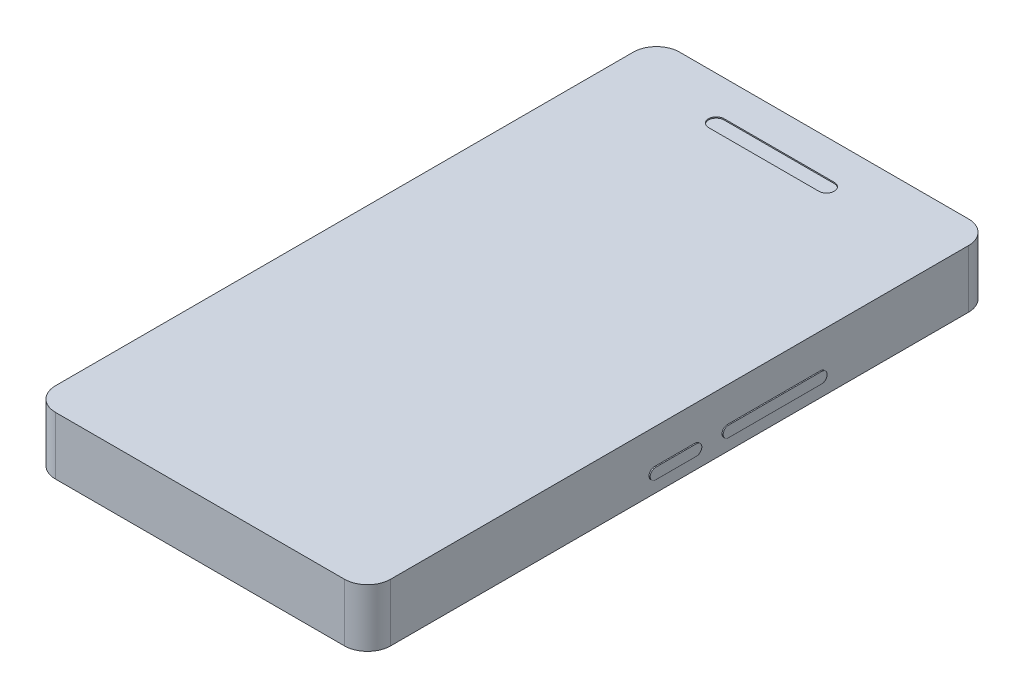
SolidWorks part; units mm, degrees
ref_plane "Front Plane" through (0, 0, 0) normal (0, 0, 1) x (1, 0, 0)
ref_plane "Top Plane" through (0, 0, 0) normal (0, 1, 0) x (1, 0, 0)
ref_plane "Right Plane" through (0, 0, 0) normal (1, 0, 0) x (0, 0, -1)
sketch "Sketch2" plane through (0, 0, 0) normal (0, 1, 0) x (1, 0, 0)
  line L1 (23.3045, 59.8762) -> (-40.1955, 59.8762)
  line L2 (28.3845, 54.7962) -> (28.3845, -72.2038)
  line L3 (23.3045, -77.2838) -> (-40.1955, -77.2838)
  line L4 (-45.2755, 54.7962) -> (-45.2755, -72.2038)
  line L5 (28.3845, 59.8762) -> (27.3244, 57.9021) construction
  line L7 (-44.2154, 57.9021) -> (-45.2755, 59.8762) construction
  arc A0 (23.3045, 59.8762) -> (28.3845, 54.7962) centre (23.3045, 54.7962) cw
  arc A1 (28.3845, -72.2038) -> (23.3045, -77.2838) centre (23.3045, -72.2038) cw
  arc A2 (-40.1955, -77.2838) -> (-45.2755, -72.2038) centre (-40.1955, -72.2038) cw
  arc A3 (-40.1955, 59.8762) -> (-45.2755, 54.7962) centre (-40.1955, 54.7962) ccw
  point P0 (-8.4455, -8.7038)
  dimension "D1" = 5.08
  dimension "D2" = 63.5
  dimension "D3" = 127
extrude "Boss-Extrude1" add sketch "Sketch2" along normal blind 12.7
sketch "Sketch5" plane through (0, 0, 0) normal (0, -1, 0) x (-1, 0, 0)
  line L0 (8.2564, 20.3242) -> (8.2564, 47.1774) construction
  line L1 (1.2594, 20.3242) -> (1.2594, 47.1774)
  line L2 (15.2534, 20.3242) -> (15.2534, 47.1774)
  arc A0 (1.2594, 20.3242) -> (15.2534, 20.3242) centre (8.2564, 20.3242) ccw
  arc A1 (15.2534, 47.1774) -> (1.2594, 47.1774) centre (8.2564, 47.1774) ccw
  point P2 (8.2564, 33.7508)
  dimension "D1" = 13.994
  dimension "D2" = 40.8472
extrude "Boss-Extrude2" add sketch "Sketch5" along normal blind 1.016
sketch "Sketch7" plane through (0, -1.016, 0) normal (0, -1, 0) x (-1, 0, 0)
  circle A0 centre (8.2564, 45.3954) radius 5.1905
sketch "Sketch8" plane through (0, -1.016, 0) normal (0, -1, 0) x (-1, 0, 0)
  circle A0 centre (8.2564, 29.8719) radius 3.7822
  circle A2 centre (8.2564, 20.3242) radius 0.5335
extrude "Cut-Extrude2" cut sketch "Sketch8" along normal blind 0.254 and the other way blind 0.254
extrude "Cut-Extrude3" cut sketch "Sketch7" against normal blind 0.254 contours A0
sketch "Sketch10" plane through (0, 12.7, 0) normal (0, 1, 0) x (1, 0, 0)
  line L0 (-22.6286, 50.3923) -> (1.5772, 50.3923) construction
  line L1 (-22.6286, 52.0942) -> (1.5772, 52.0942)
  line L2 (-22.6286, 48.6903) -> (1.5772, 48.6903)
  arc A0 (-22.6286, 52.0942) -> (-22.6286, 48.6903) centre (-22.6286, 50.3923) ccw
  arc A1 (1.5772, 48.6903) -> (1.5772, 52.0942) centre (1.5772, 50.3923) ccw
  point P2 (-10.5257, 50.3923)
  dimension "D1" = 3.4039
  dimension "D2" = 27.6097
  dimension "D3" = 24.2058
extrude "Cut-Extrude5" cut sketch "Sketch10" against normal blind 0.254
sketch "Sketch11" plane through (0, 12.7, 0) normal (0, 1, 0) x (1, 0, 0)
  circle A0 centre (9.2418, 50.3923) radius 1.7177
sketch "Sketch12" plane through (0, 12.7, 0) normal (0, 1, 0) x (1, 0, 0)
  line L4 (-43.8485, -57.7538) -> (-43.8485, 42.9966)
  line L5 (24.0389, -60.2938) -> (-41.3085, -60.2938)
  line L6 (26.5789, -57.7538) -> (26.5789, 42.9966)
  line L9 (26.5789, -60.2938) -> (-43.8485, 45.5366) construction
  line L10 (26.5789, 45.5366) -> (-43.8485, -60.2938) construction
  line L11 (24.0389, 45.5366) -> (-41.3085, 45.5366)
  line L12 (-30.8881, 50.3424) -> (-27.3288, 50.3424) construction
  line L13 (-30.8881, 50.8368) -> (-27.3288, 50.8368)
  line L14 (-30.8881, 49.8481) -> (-27.3288, 49.8481)
  line L15 (15.7926, -65.7218) -> (15.7926, -70.8018)
  line L23 (11.9826, -70.8018) -> (9.0594, -68.1653)
  line L24 (9.0594, -68.1653) -> (11.9826, -65.7218)
  line L25 (15.7926, -65.7218) -> (11.9826, -65.7218)
  line L26 (11.9826, -70.8018) -> (15.7926, -70.8018)
  line L27 (-33.2978, -65.5689) -> (-28.4783, -65.5689)
  line L28 (-33.2978, -65.5689) -> (-33.2978, -70.7437)
  line L29 (-33.2978, -70.7437) -> (-28.4783, -70.7437)
  line L30 (-28.4783, -65.5689) -> (-28.4783, -70.7437)
  line L31 (-33.2978, -65.5689) -> (-28.4783, -70.7437) construction
  line L32 (-33.2978, -70.7437) -> (-28.4783, -65.5689) construction
  arc A0 (-41.3085, 45.5366) -> (-43.8485, 42.9966) centre (-41.3085, 42.9966) ccw
  arc A1 (26.5789, 42.9966) -> (24.0389, 45.5366) centre (24.0389, 42.9966) ccw
  arc A2 (24.0389, -60.2938) -> (26.5789, -57.7538) centre (24.0389, -57.7538) ccw
  arc A3 (-41.3085, -60.2938) -> (-43.8485, -57.7538) centre (-41.3085, -57.7538) cw
  arc A4 (-30.8881, 50.8368) -> (-30.8881, 49.8481) centre (-30.8881, 50.3424) ccw
  arc A5 (-27.3288, 49.8481) -> (-27.3288, 50.8368) centre (-27.3288, 50.3424) ccw
  circle A6 centre (-9.1256, -68.1563) radius 2.5874
  point P0 (-8.6348, -7.3786)
  point P7 (-29.1084, 50.3424)
  point P24 (-30.8881, -68.1563)
  dimension "D1" = 2.54
  dimension "D6" = 5.1749
  dimension "D2" = 65.3473
  dimension "D3" = 0.9887
  dimension "D4" = 3.5593
  dimension "D5" = 5.1749
  dimension "D7" = 5.08
  dimension "D8" = 3.81
  dimension "D9" = 3.9365
  dimension "D10" = 3.81
  dimension "D11" = 3.81
sketch "Sketch13" plane through (0, 0, -59.8762) normal (0, 0, -1) x (-1, 0, 0)
  circle A0 centre (26.0982, 2.9935) radius 2.8931
extrude "Cut-Extrude7" cut sketch "Sketch13" against normal blind 11.43
sketch "Sketch14" plane through (0, 0, -59.8762) normal (0, 0, -1) x (-1, 0, 0)
  line L0 (4.1853, 2.9789) -> (13.7518, 2.9789) construction
  line L1 (4.1853, 5.3074) -> (13.7518, 5.3074)
  line L2 (4.1853, 0.6504) -> (13.7518, 0.6504)
  line L3 (4.1853, 2.9789) -> (13.7518, 2.9789) construction
  line L4 (4.1853, 3.8128) -> (13.7518, 3.8128)
  line L5 (4.1853, 2.145) -> (13.7518, 2.145)
  arc A0 (4.1853, 5.3074) -> (4.1853, 0.6504) centre (4.1853, 2.9789) ccw
  arc A1 (13.7518, 0.6504) -> (13.7518, 5.3074) centre (13.7518, 2.9789) ccw
  arc A2 (4.1853, 3.8128) -> (4.1853, 2.145) centre (4.1853, 2.9789) ccw
  arc A3 (13.7518, 2.145) -> (13.7518, 3.8128) centre (13.7518, 2.9789) ccw
  point P2 (8.9686, 2.9789)
  point P9 (8.9686, 2.9789)
  dimension "D1" = 4.657
  dimension "D2" = 14.2235
  dimension "D3" = 1.6678
  dimension "D4" = 9.5665
extrude "Cut-Extrude8" cut sketch "Sketch14" against normal blind 7.62
sketch "Sketch16" plane through (28.3845, 0, 0) normal (1, 0, 0) x (0, 0, -1)
  line L0 (1.8126, 3.9435) -> (22.282, 3.9435) construction
  line L1 (1.8126, 5.1388) -> (22.282, 5.1388)
  line L2 (1.8126, 2.7482) -> (22.282, 2.7482)
  line L3 (-14.2262, 3.9435) -> (-5.2615, 3.9435) construction
  line L4 (-14.2262, 5.1388) -> (-5.2615, 5.1388)
  line L5 (-14.2262, 2.7482) -> (-5.2615, 2.7482)
  arc A0 (1.8126, 5.1388) -> (1.8126, 2.7482) centre (1.8126, 3.9435) ccw
  arc A1 (22.282, 2.7482) -> (22.282, 5.1388) centre (22.282, 3.9435) ccw
  arc A2 (-14.2262, 5.1388) -> (-14.2262, 2.7482) centre (-14.2262, 3.9435) ccw
  arc A3 (-5.2615, 2.7482) -> (-5.2615, 5.1388) centre (-5.2615, 3.9435) ccw
  point P2 (12.0473, 3.9435)
  point P9 (-9.7439, 3.9435)
  dimension "D1" = 2.3906
  dimension "D2" = 22.86
  dimension "D3" = 2.3906
  dimension "D4" = 11.3553
extrude "Boss-Extrude3" add sketch "Sketch16" along normal blind 0.254
sketch "Sketch17" plane through (0, 0, 0) normal (0, 1, 0) x (1, 0, 0)
